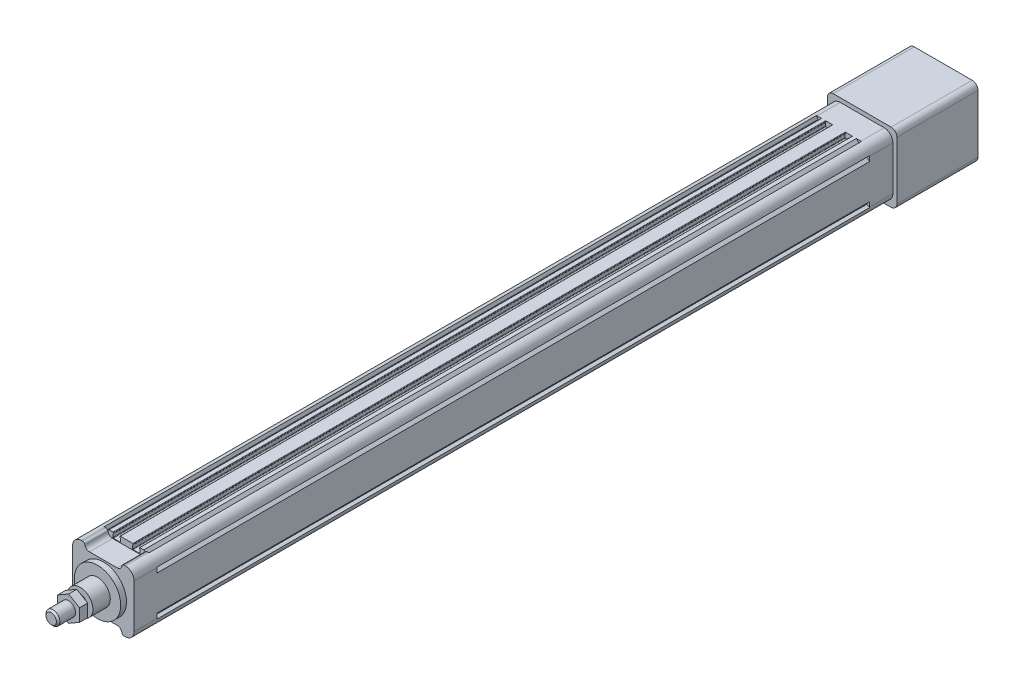
SolidWorks part; units mm, degrees
ref_plane "Front" through (0, 0, 0) normal (0, 0, 1) x (1, 0, 0)
ref_plane "Top" through (0, 0, 0) normal (0, 1, 0) x (1, 0, 0)
ref_plane "Right" through (0, 0, 0) normal (1, 0, 0) x (0, 0, -1)
sketch "草图1" plane through (0, 0, 0) normal (0, 0, 1) x (1, 0, 0)
  line L0 (19.7737, 3) -> (23.3, 3)
  line L1 (23.3, 3) -> (23.3, -3)
  line L2 (23.3, -3) -> (19.7737, -3)
  line L3 (-19.7737, -3) -> (-23.3, -3)
  line L4 (-23.3, -3) -> (-23.3, 3)
  line L5 (-23.3, 3) -> (-19.7737, 3)
  line L6 (-18.2, 24) -> (-19.4434, 26.4869)
  line L7 (-26.4869, 19.4434) -> (-24, 18.2)
  line L8 (-24, 18.2) -> (-24, 17.1)
  line L9 (-24, 17.1) -> (-26.5, 15)
  line L10 (-26.5, 15) -> (-26.5, -15)
  line L11 (-26.5, -15) -> (-24, -17.1)
  line L12 (-24, -17.1) -> (-24, -18.2)
  line L13 (-24, -18.2) -> (-26.4869, -19.4434)
  line L14 (-19.4434, -26.4869) -> (-18.2, -24)
  line L15 (-18.2, -24) -> (-17.1, -24)
  line L16 (-17.1, -24) -> (-15, -26.5)
  line L17 (-15, -26.5) -> (-11.65, -26.5)
  line L18 (-11.25, -26.1) -> (-11.25, -25.6)
  line L19 (-11.65, -25.2) -> (-11.75, -25.2)
  line L20 (-11.75, -25.2) -> (-11.75, -22.4)
  line L21 (-11.35, -22) -> (-5.65, -22)
  line L22 (-5.25, -22.4) -> (-5.25, -25.2)
  line L23 (-5.25, -25.2) -> (-5.35, -25.2)
  line L24 (-5.75, -25.6) -> (-5.75, -26.1)
  line L25 (-5.35, -26.5) -> (5.35, -26.5)
  line L26 (5.75, -26.1) -> (5.75, -25.6)
  line L27 (5.35, -25.2) -> (5.25, -25.2)
  line L28 (5.25, -25.2) -> (5.25, -22.4)
  line L29 (5.65, -22) -> (11.35, -22)
  line L30 (11.75, -22.4) -> (11.75, -25.2)
  line L31 (11.75, -25.2) -> (11.65, -25.2)
  line L32 (11.25, -25.6) -> (11.25, -26.1)
  line L33 (11.65, -26.5) -> (15, -26.5)
  line L34 (15, -26.5) -> (17.1, -24)
  line L35 (17.1, -24) -> (18.2, -24)
  line L36 (18.2, -24) -> (19.4434, -26.4869)
  line L37 (26.4869, -19.4434) -> (24, -18.2)
  line L38 (24, -18.2) -> (24, -17.1)
  line L39 (24, -17.1) -> (26.5, -15)
  line L40 (26.5, -15) -> (26.5, 15)
  line L41 (26.5, 15) -> (24, 17.1)
  line L42 (24, 17.1) -> (24, 18.2)
  line L43 (24, 18.2) -> (26.4869, 19.4434)
  line L44 (19.4434, 26.4869) -> (18.2, 24)
  line L45 (18.2, 24) -> (17.1, 24)
  line L46 (17.1, 24) -> (15, 26.5)
  line L47 (15, 26.5) -> (11.65, 26.5)
  line L48 (11.25, 26.1) -> (11.25, 25.6)
  line L49 (11.65, 25.2) -> (11.75, 25.2)
  line L50 (11.75, 25.2) -> (11.75, 22.4)
  line L51 (11.35, 22) -> (5.65, 22)
  line L52 (5.25, 22.4) -> (5.25, 25.2)
  line L53 (5.25, 25.2) -> (5.35, 25.2)
  line L54 (5.75, 25.6) -> (5.75, 26.1)
  line L55 (5.35, 26.5) -> (-5.35, 26.5)
  line L56 (-5.75, 26.1) -> (-5.75, 25.6)
  line L57 (-5.35, 25.2) -> (-5.25, 25.2)
  line L58 (-5.25, 25.2) -> (-5.25, 22.4)
  line L59 (-5.65, 22) -> (-11.35, 22)
  line L60 (-11.75, 22.4) -> (-11.75, 25.2)
  line L61 (-11.75, 25.2) -> (-11.65, 25.2)
  line L62 (-11.25, 25.6) -> (-11.25, 26.1)
  line L63 (-11.65, 26.5) -> (-15, 26.5)
  line L64 (-15, 26.5) -> (-17.1, 24)
  line L65 (-17.1, 24) -> (-18.2, 24)
  arc A0 (19.7737, 3) -> (-19.7737, 3) centre (0, 0) ccw
  arc A1 (-19.7737, -3) -> (19.7737, -3) centre (0, 0) ccw
  circle A2 centre (19, 19) radius 2.1
  circle A3 centre (19, -19) radius 2.1
  circle A4 centre (-19, -19) radius 2.1
  circle A5 centre (-19, 19) radius 2.1
  arc A6 (-19.4434, 26.4869) -> (-26.4869, 19.4434) centre (-19, 19) ccw
  arc A7 (-26.4869, -19.4434) -> (-19.4434, -26.4869) centre (-19, -19) ccw
  arc A8 (-11.65, -26.5) -> (-11.25, -26.1) centre (-11.65, -26.1) ccw
  arc A9 (-11.25, -25.6) -> (-11.65, -25.2) centre (-11.65, -25.6) ccw
  arc A10 (-11.35, -22) -> (-11.75, -22.4) centre (-11.35, -22.4) ccw
  arc A11 (-5.25, -22.4) -> (-5.65, -22) centre (-5.65, -22.4) ccw
  arc A12 (-5.35, -25.2) -> (-5.75, -25.6) centre (-5.35, -25.6) ccw
  arc A13 (-5.75, -26.1) -> (-5.35, -26.5) centre (-5.35, -26.1) ccw
  arc A14 (5.35, -26.5) -> (5.75, -26.1) centre (5.35, -26.1) ccw
  arc A15 (5.75, -25.6) -> (5.35, -25.2) centre (5.35, -25.6) ccw
  arc A16 (5.65, -22) -> (5.25, -22.4) centre (5.65, -22.4) ccw
  arc A17 (11.75, -22.4) -> (11.35, -22) centre (11.35, -22.4) ccw
  arc A18 (11.65, -25.2) -> (11.25, -25.6) centre (11.65, -25.6) ccw
  arc A19 (11.25, -26.1) -> (11.65, -26.5) centre (11.65, -26.1) ccw
  arc A20 (19.4434, -26.4869) -> (26.4869, -19.4434) centre (19, -19) ccw
  arc A21 (26.4869, 19.4434) -> (19.4434, 26.4869) centre (19, 19) ccw
  arc A22 (11.65, 26.5) -> (11.25, 26.1) centre (11.65, 26.1) ccw
  arc A23 (11.25, 25.6) -> (11.65, 25.2) centre (11.65, 25.6) ccw
  arc A24 (11.35, 22) -> (11.75, 22.4) centre (11.35, 22.4) ccw
  arc A25 (5.25, 22.4) -> (5.65, 22) centre (5.65, 22.4) ccw
  arc A26 (5.35, 25.2) -> (5.75, 25.6) centre (5.35, 25.6) ccw
  arc A27 (5.75, 26.1) -> (5.35, 26.5) centre (5.35, 26.1) ccw
  arc A28 (-5.35, 26.5) -> (-5.75, 26.1) centre (-5.35, 26.1) ccw
  arc A29 (-5.75, 25.6) -> (-5.35, 25.2) centre (-5.35, 25.6) ccw
  arc A30 (-5.65, 22) -> (-5.25, 22.4) centre (-5.65, 22.4) ccw
  arc A31 (-11.75, 22.4) -> (-11.35, 22) centre (-11.35, 22.4) ccw
  arc A32 (-11.65, 25.2) -> (-11.25, 25.6) centre (-11.65, 25.6) ccw
  arc A33 (-11.25, 26.1) -> (-11.65, 26.5) centre (-11.65, 26.1) ccw
extrude "凸台-拉伸1" add sketch "草图1" along normal blind 615
sketch "草图6" plane through (0, 0, 615) normal (0, 0, 1) x (1, 0, 0)
  line L0 (0, 0) -> (19, 0) construction
  line L2 (-26.5, -19) -> (-26.5, 19)
  line L3 (-19, 26.5) -> (-17.9161, 26.5)
  line L4 (26.5, -19) -> (26.5, 19)
  line L5 (-26.5, -26.5) -> (26.5, 26.5) construction
  line L6 (-26.5, 26.5) -> (26.5, -26.5) construction
  line L7 (-12, 21.5) -> (12, 21.5)
  line L9 (19, 26.5) -> (17.9161, 26.5)
  line L10 (19, -26.5) -> (17.9161, -26.5)
  line L11 (-12, -21.5) -> (12, -21.5)
  line L12 (-19, -26.5) -> (-17.9161, -26.5)
  arc A0 (12, 21.5) -> (15.9441, 24.8333) centre (12, 25.5) ccw
  arc A1 (-15.9441, 24.8333) -> (-12, 21.5) centre (-12, 25.5) ccw
  arc A2 (-15.9441, 24.8333) -> (-17.9161, 26.5) centre (-17.9161, 24.5) ccw
  arc A3 (15.9441, 24.8333) -> (17.9161, 26.5) centre (17.9161, 24.5) cw
  arc A4 (-26.5, -19) -> (-19, -26.5) centre (-19, -19) ccw
  arc A5 (19, -26.5) -> (26.5, -19) centre (19, -19) ccw
  arc A6 (26.5, 19) -> (19, 26.5) centre (19, 19) ccw
  arc A7 (-26.5, 19) -> (-19, 26.5) centre (-19, 19) cw
  arc A8 (15.9441, -24.8333) -> (17.9161, -26.5) centre (17.9161, -24.5) ccw
  arc A9 (12, -21.5) -> (15.9441, -24.8333) centre (12, -25.5) cw
  arc A10 (-15.9441, -24.8333) -> (-12, -21.5) centre (-12, -25.5) cw
  arc A11 (-15.9441, -24.8333) -> (-17.9161, -26.5) centre (-17.9161, -24.5) cw
  point P0 (0, 0)
  point P9 (0, 21.5)
  point P13 (20, 20.8461)
  point P16 (-12, 20.8461)
  dimension "D5" = 4
  dimension "D6" = 2
  dimension "D7" = 2
  dimension "D9" = 7.5
  dimension "D1" = 53
  dimension "D2" = 53
  dimension "D3" = 26.5
  dimension "D4" = 24
  dimension "D8" = 5
extrude "凸台-拉伸2" add sketch "草图6" along normal blind 20
sketch "草图7" plane through (0, 0, 635) normal (0, 0, 1) x (1, 0, 0)
  circle A0 centre (0, 0) radius 20
  dimension "D1" = 40
extrude "凸台-拉伸3" add sketch "草图7" along normal blind 5
sketch "草图9" plane through (0, 0, 640) normal (0, 0, 1) x (1, 0, 0)
  circle A0 centre (0, 0) radius 11
  dimension "D1" = 22
extrude "凸台-拉伸4" add sketch "草图9" along normal blind 15
sketch "草图10" plane through (0, 0, 655) normal (0, 0, 1) x (1, 0, 0)
  circle A0 centre (0, 0) radius 6
  dimension "D1" = 12
extrude "凸台-拉伸5" add sketch "草图10" along normal blind 25
sketch "草图11" plane through (0, 0, 0) normal (0, 0, -1) x (-1, 0, 0)
  line L1 (-19, -26.5) -> (19, -26.5)
  line L2 (-26.5, -19) -> (-26.5, 19)
  line L3 (-19, 26.5) -> (19, 26.5)
  line L4 (26.5, -19) -> (26.5, 19)
  line L5 (-26.5, -26.5) -> (26.5, 26.5) construction
  line L6 (-26.5, 26.5) -> (26.5, -26.5) construction
  arc A0 (-26.5, -19) -> (-19, -26.5) centre (-19, -19) ccw
  arc A1 (19, -26.5) -> (26.5, -19) centre (19, -19) ccw
  arc A2 (26.5, 19) -> (19, 26.5) centre (19, 19) ccw
  arc A3 (-26.5, 19) -> (-19, 26.5) centre (-19, 19) cw
  point P0 (0, 0)
  dimension "D3" = 7.5
  dimension "D1" = 53
  dimension "D2" = 53
extrude "凸台-拉伸6" add sketch "草图11" along normal blind 20
sketch "草图12" plane through (0, 0, -20) normal (0, 0, -1) x (-1, 0, 0)
  line L1 (-25, -30) -> (25, -30)
  line L2 (-30, -25) -> (-30, 25)
  line L3 (-25, 30) -> (25, 30)
  line L4 (30, -25) -> (30, 25)
  line L5 (-30, -30) -> (30, 30) construction
  line L6 (-30, 30) -> (30, -30) construction
  arc A0 (-30, -25) -> (-25, -30) centre (-25, -25) ccw
  arc A1 (25, -30) -> (30, -25) centre (25, -25) ccw
  arc A2 (30, 25) -> (25, 30) centre (25, 25) ccw
  arc A3 (-30, 25) -> (-25, 30) centre (-25, 25) cw
  point P0 (0, 0)
  dimension "D3" = 5
  dimension "D1" = 60
  dimension "D2" = 60
extrude "凸台-拉伸7" add sketch "草图12" along normal blind 70
sketch "草图14" plane through (0, 0, -90) normal (0, 0, -1) x (-1, 0, 0)
  circle A0 centre (0, 0) radius 19
  dimension "D1" = 38
extrude "切除-拉伸2" cut sketch "草图14" against normal blind 70
hole_wizard "M6 螺纹孔1" positions "草图15" profile "草图16" tap size "M6" standard "GB"
sketch "草图15" plane through (-26.5, 0, 0) normal (-1, 0, 0) x (0, 0, 1)
  line L0 (-20, -25) -> (-20, 25) construction
  line L1 (635, 19) -> (635, -19) construction
  point P0 (625, 11)
  point P2 (625, -11)
  point P4 (-10, 11)
  point P6 (-10, -11)
  dimension "D1" = 10
  dimension "D2" = 10
  dimension "D3" = 11
  dimension "D4" = 11
  dimension "D5" = 10
  dimension "D6" = 10
  dimension "D7" = 22
  dimension "D8" = 11
sketch "草图16" plane through (-26.5, 11, 625) normal (0, 1, 0) x (0, 0, 1)
  line L0 (0, 0) -> (0, 16.5022)
  line L1 (0, 16.5022) -> (2.5, 15)
  line L2 (2.5, 15) -> (2.5, 0)
  line L5 (2.5, 0) -> (0, 0)
  line L10 (0, 16.5022) -> (-2.5, 15) construction
  line L11 (0, -6.35) -> (0, 107.95) construction
  dimension "螺纹孔钻头直径" = 5
  dimension "螺纹孔钻头深度" = 15
  dimension "导头角度" = 118
cosmetic thread "孔螺蚊线4" parameters "D1"=12, "D2"=6
cosmetic thread "孔螺蚊线5" parameters "D1"=12, "D2"=6
cosmetic thread "孔螺蚊线6" parameters "D1"=12, "D2"=6
cosmetic thread "孔螺蚊线7" parameters "D1"=12, "D2"=6
chamfer "倒角1" distance 1.5 angle 45 1 edges at (6, 0, 680)
sketch "草图17" plane through (0, 0, 655) normal (0, 0, 1) x (1, 0, 0)
  line L1 (0, 10.9697) -> (-9.5, 5.4848)
  line L2 (-9.5, 5.4848) -> (-9.5, -5.4848)
  line L3 (-9.5, -5.4848) -> (0, -10.9697)
  line L4 (0, -10.9697) -> (9.5, -5.4848)
  line L5 (9.5, -5.4848) -> (9.5, 5.4848)
  line L6 (9.5, 5.4848) -> (0, 10.9697)
  circle A0 centre (0, 0) radius 9.5 construction
  dimension "D1" = 19
extrude "凸台-拉伸8" add sketch "草图17" along normal blind 7 from offset 3
